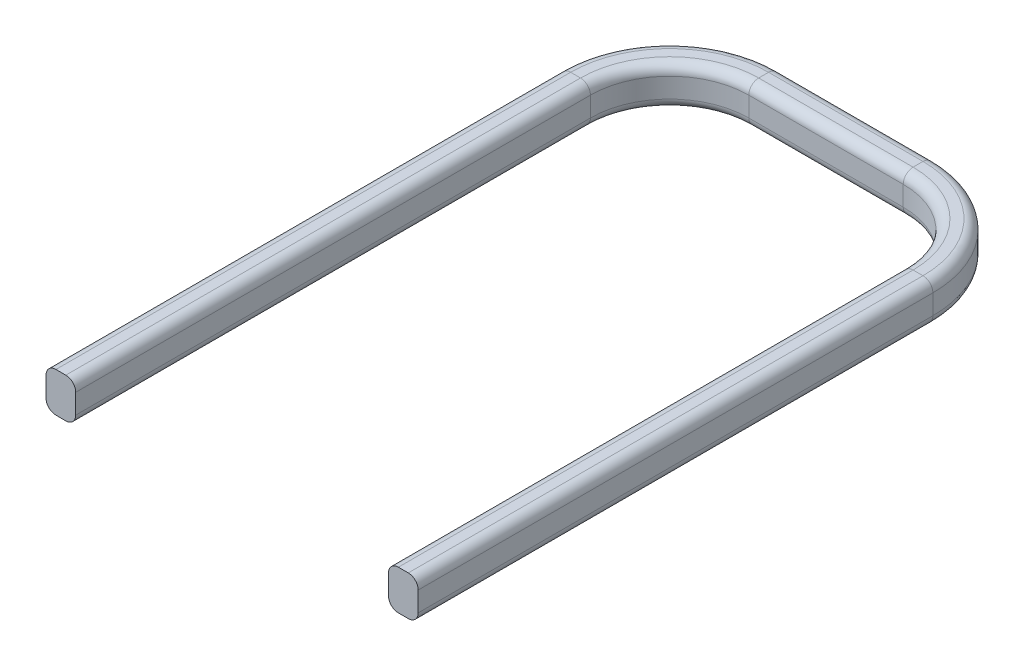
SolidWorks part; units mm, degrees
ref_plane "Front Plane" through (0, 0, 0) normal (0, 0, 1) x (1, 0, 0)
ref_plane "Top Plane" through (0, 0, 0) normal (0, 1, 0) x (1, 0, 0)
ref_plane "Right Plane" through (0, 0, 0) normal (1, 0, 0) x (0, 0, -1)
sketch "Sketch1" plane through (0, 0, 0) normal (0, 1, 0) x (1, 0, 0)
  line L0 (-3.95, 0) -> (-3.95, 13)
  line L1 (-1.95, 15) -> (1.95, 15)
  line L2 (0, 24.115) -> (0, -17.1815) construction
  line L3 (3.95, 0) -> (3.95, 13)
  arc A0 (-3.95, 13) -> (-1.95, 15) centre (-1.95, 13) cw
  arc A1 (3.95, 13) -> (1.95, 15) centre (1.95, 13) ccw
  point P6 (-3.95, 15)
  point P10 (0, 15)
  dimension "D3" = 2
  dimension "D1" = 3.95
  dimension "D2" = 15
sketch "Sketch2" plane through (0, 0, 0) normal (0, 0, 1) x (1, 0, 0)
  line L1 (-3.95, 0) -> (-4.7, 0)
  line L2 (-3.95, 0) -> (-3.95, 1)
  line L3 (-3.95, 1) -> (-4.7, 1)
  line L4 (-4.7, 0) -> (-4.7, 1)
  dimension "D1" = 1
  dimension "D2" = 0.75
sweep "Sweep1" add profiles "Sketch2" path "Sketch1"
fillet "Fillet1" radius 0.25 20 edges at (3.95, 0, -6.5) (3.3642, 0, -14.4142) (0, 0, -15) (-3.3642, 0, -14.4142) (-4.7, 0, -6.5) (-3.8945, 0, -14.9445) (0, 0, -15.75) (3.8945, 0, -14.9445) (-4.7, 1, -6.5) (-3.8945, 1, -14.9445) (0, 1, -15.75) (3.8945, 1, -14.9445) (3.95, 1, -6.5) (3.3642, 1, -14.4142) (0, 1, -15) (-3.3642, 1, -14.4142) (-3.95, 0, -6.5) (4.7, 0, -6.5) (4.7, 1, -6.5) (-3.95, 1, -6.5)
